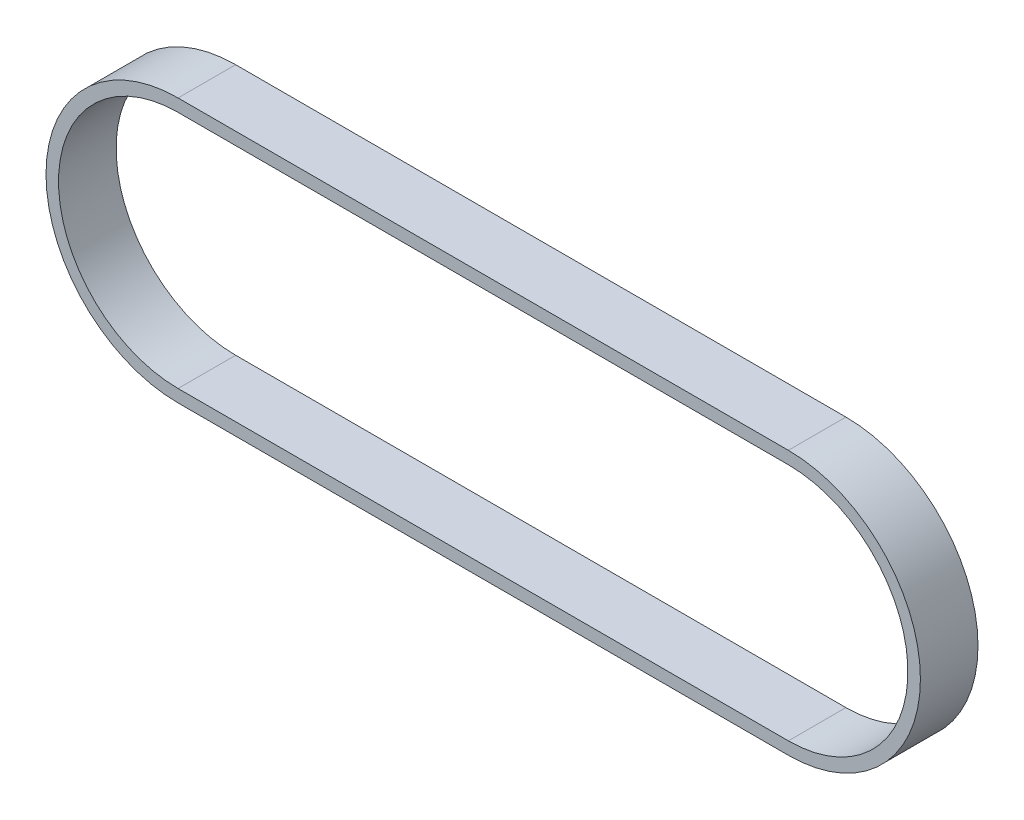
SolidWorks part; units mm, degrees
ref_plane "Front Plane" through (0, 0, 0) normal (0, 0, 1) x (1, 0, 0)
ref_plane "Top Plane" through (0, 0, 0) normal (0, 1, 0) x (1, 0, 0)
ref_plane "Right Plane" through (0, 0, 0) normal (1, 0, 0) x (0, 0, -1)
sketch "Sketch1" plane through (0, 0, 0) normal (0, 0, 1) x (1, 0, 0)
  line L0 (0, 0) -> (97.5, 0) construction
  line L1 (0, 19.1) -> (97.5, 19.1)
  line L2 (0, -19.1) -> (97.5, -19.1)
  circle A0 centre (0, 0) radius 19.1 construction
  circle A1 centre (97.5, 0) radius 19.1 construction
  arc A2 (97.5, -19.1) -> (97.5, 19.1) centre (97.5, 0) ccw
  arc A3 (0, 19.1) -> (0, -19.1) centre (0, 0) ccw
  dimension "D2" = 38.2
  dimension "D1" = 97.5
extrude "Extrude-Thin1" add sketch "Sketch1" along normal blind 9.2 thin thin type one direction wall 2
equation "\"pitchDiameter\"= 38.2mm"
equation "\"pulley2pulleyDistance\"= 97.5mm"
equation "\"D1@Sketch1\"=\"pulley2pulleyDistance\""
equation "\"D2@Sketch1\"=\"pitchDiameter\""
